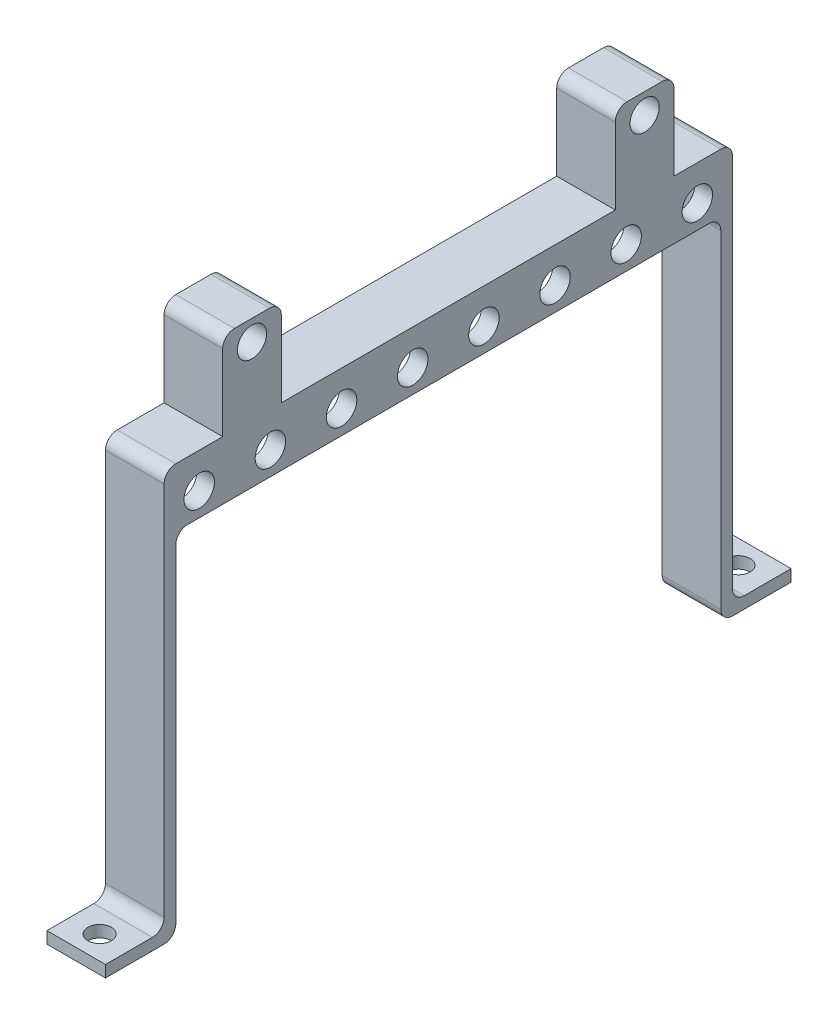
SolidWorks part; units mm, degrees
ref_plane "Front Plane" through (0, 0, 0) normal (0, 0, 1) x (1, 0, 0)
ref_plane "Top Plane" through (0, 0, 0) normal (0, 1, 0) x (1, 0, 0)
ref_plane "Right Plane" through (0, 0, 0) normal (1, 0, 0) x (0, 0, -1)
sketch "Sketch1" plane through (0, 0, 0) normal (1, 0, 0) x (0, 0, -1)
  line L0 (-58.5, 0) -> (-46.5, 0)
  line L1 (-46.5, 0) -> (-46.5, 68)
  line L2 (-46.5, 68) -> (0, 68)
  line L3 (0, 0) -> (0, 68) construction
  line L4 (-58.5, 2) -> (-48.5, 2)
  line L5 (-48.5, 2) -> (-48.5, 70)
  line L6 (-48.5, 70) -> (0, 70)
  line L7 (-58.5, 0) -> (-58.5, 2)
  line L8 (0, 68) -> (0, 70)
  line L9 (-53.5, 2) -> (-53.5, 0) construction
  line L11 (-38.5, 70) -> (-28.5, 70)
  line L12 (-38.5, 70) -> (-38.5, 85)
  line L13 (-38.5, 85) -> (-28.5, 85)
  line L14 (-28.5, 70) -> (-28.5, 85)
  circle A0 centre (-33.5, 81.5) radius 2.5
  dimension "D10" = 5
  dimension "D2" = 53.5
  dimension "D3" = 10
  dimension "D4" = 70
  dimension "D5" = 10
  dimension "D6" = 10
  dimension "D7" = 15
  dimension "D8" = 3.5
  dimension "D9" = 5
  dimension "D1" = 2
extrude "Boss-Extrude1" add sketch "Sketch1" along normal blind 10 contours L2 L8 L6 L5 L4 L7 L0 L1 | L6 L14 L13 L12 A0
fillet "Fillet1" radius 2 2 edges at (5, 70, 48.5) (5, 2, 48.5)
hole_wizard "Ø4.0mm Dowel Hole1" positions "3DSketch1" profile "Sketch2" hole size "Ø4.0" standard "DIN" end condition through all
sketch3d "3DSketch1"
  line L0 (5, 2, 54.5) -> (5, 2, 50.5) construction
  line L1 (10, 2, 50.5) -> (0, 2, 50.5) construction
  line L3 (5, 2, 54.5) -> (10, 2, 54.5) construction
  point P0 (5, 2, 54.5)
  point P12 (0, 0, 0)
sketch "Sketch2" plane through (5, 2, 54.5) normal (1, 0, 0) x (0, 0, 1)
  line L0 (0, 0) -> (0, 2)
  line L1 (0, 2) -> (2, 2)
  line L2 (2, 2) -> (2, 0)
  line L5 (2, 0) -> (0, 0)
  line L11 (0, -6.35) -> (0, 107.95) construction
  dimension "Thru Hole Dia." = 4
  dimension "Thru Hole Depth" = 2
mirror "Mirror1" about plane through (0, 0, 0) normal (0, 0, 1) of "Fillet1", "Ø4.0mm Dowel Hole1", "Boss-Extrude1"
sketch "Sketch4" plane through (10, 0, 0) normal (1, 0, 0) x (0, 0, -1)
  line L1 (-46.5, 68) -> (46.5, 68)
  line L2 (-46.5, 68) -> (-46.5, 60)
  line L3 (-46.5, 60) -> (46.5, 60)
  line L4 (46.5, 68) -> (46.5, 60)
  circle A0 centre (-42.5, 64) radius 2.6
  circle A1 centre (-30.3571, 64) radius 2.6
  circle A2 centre (-18.2143, 64) radius 2.6
  circle A3 centre (-6.0714, 64) radius 2.6
  circle A4 centre (6.0714, 64) radius 2.6
  circle A5 centre (18.2143, 64) radius 2.6
  circle A6 centre (30.3571, 64) radius 2.6
  circle A7 centre (42.5, 64) radius 2.6
  point P4 (0, 0)
  point P5 (0, 0)
  point P9 (0, 0)
  point P10 (0, 0)
  point P25 (0, 0)
  point P26 (0, 0)
  point P27 (0, 0)
  dimension "D3" = 5.2
  dimension "D1" = 4
  dimension "D2" = 4
  dimension "D4" = 4
  dimension "D6" = 4
  dimension "D5" = 8
extrude "Boss-Extrude2" add sketch "Sketch4" against normal blind 3
fillet "Fillet2" radius 2 10 edges at (8.5, 60, -46.5) (3.5, 68, -46.5) (3.5, 68, 46.5) (5, 0, 46.5) (5, 0, -46.5) (8.5, 60, 46.5) (5, 85, -38.5) (5, 85, -28.5) (5, 85, 38.5) (5, 85, 28.5)
